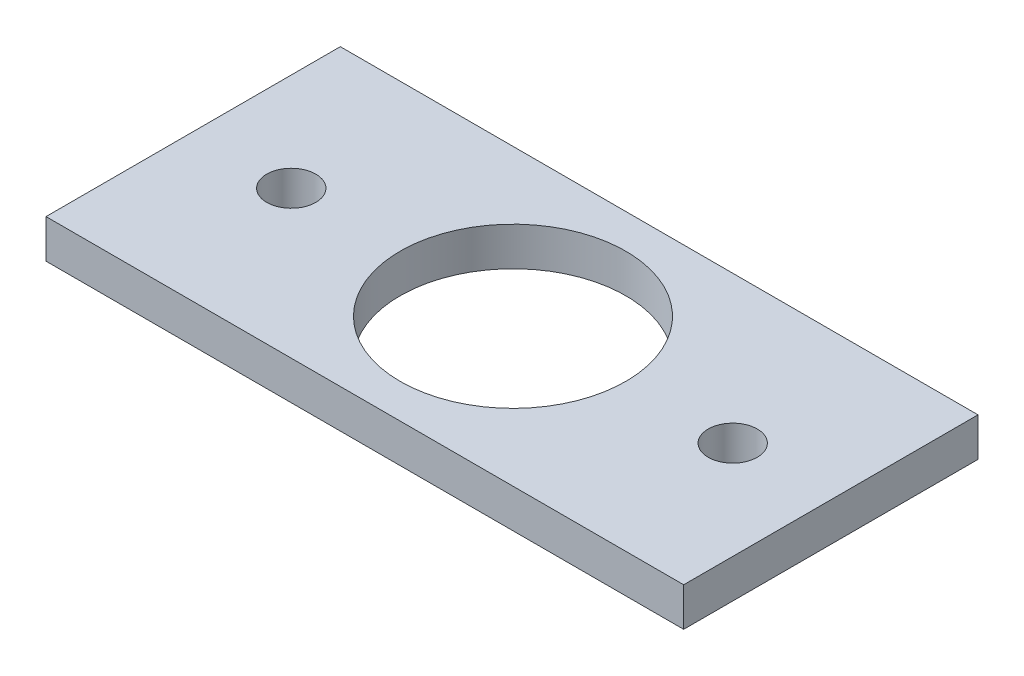
SolidWorks part; units mm, degrees
ref_plane "Front Plane" through (0, 0, 0) normal (0, 0, 1) x (1, 0, 0)
ref_plane "Top Plane" through (0, 0, 0) normal (0, 1, 0) x (1, 0, 0)
ref_plane "Right Plane" through (0, 0, 0) normal (1, 0, 0) x (0, 0, -1)
sketch "Sketch1" plane through (0, 0, 0) normal (0, 1, 0) x (1, 0, 0)
  line L1 (-41.402, 19.05) -> (41.148, 19.05)
  line L2 (-41.402, 19.05) -> (-41.402, -19.05)
  line L3 (-41.402, -19.05) -> (41.148, -19.05)
  line L4 (41.148, 19.05) -> (41.148, -19.05)
  circle A0 centre (0, 0) radius 14.605
  circle A1 centre (28.448, 0) radius 3.175
  circle A2 centre (-28.702, 0) radius 3.175
  dimension "D3" = 29.21
  dimension "D4" = 6.35
  dimension "D5" = 6.35
  dimension "D1" = 38.1
  dimension "D2" = 82.55
  dimension "D6" = 12.7
  dimension "D7" = 69.85
  dimension "D8" = 41.402
  dimension "D9" = 19.05
extrude "Boss-Extrude1" add sketch "Sketch1" along normal blind 5
